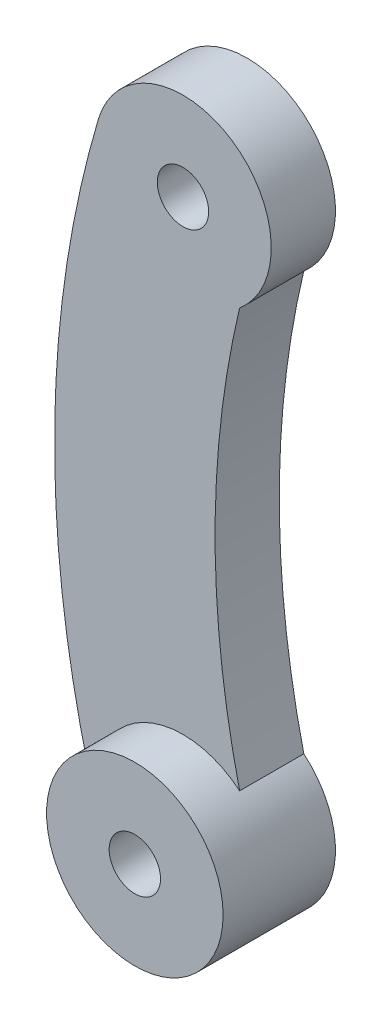
SolidWorks part; units mm, degrees
ref_plane "Ön Düzlem" through (0, 0, 0) normal (0, 0, 1) x (1, 0, 0)
ref_plane "Üst Düzlem" through (0, 0, 0) normal (0, 1, 0) x (1, 0, 0)
ref_plane "Sağ Düzlem" through (0, 0, 0) normal (1, 0, 0) x (0, 0, -1)
sketch "Çizim1" plane through (0, 0, 0) normal (0, 0, 1) x (1, 0, 0)
  line L0 (0, 34.5) -> (0, 0) construction
  line L1 (-8, 17.25) -> (34.0236, 17.25) construction
  arc A0 (-5.2737, -1.5614) -> (3.5302, 4.2175) centre (0, 0) ccw
  arc A1 (3.5302, 30.2825) -> (-5.2737, 36.0614) centre (0, 34.5) ccw
  arc A2 (-5.2737, 36.0614) -> (-5.2737, -1.5614) centre (58.2625, 17.25) ccw
  arc A3 (3.5302, 30.2825) -> (3.5302, 4.2175) centre (58.2625, 17.25) ccw
  circle A4 centre (0, 34.5) radius 1.6
  circle A5 centre (0, 0) radius 1.6
  dimension "D1" = 11
  dimension "D2" = 11
  dimension "D5" = 10
  dimension "D6" = 3.2
  dimension "D7" = 3.2
  dimension "D3" = 34.5
  dimension "D4" = 8
extrude "Yükseklik-Ekstrüzyon1" add sketch "Çizim1" along normal blind 4
sketch "Çizim2" plane through (0, 0, 4) normal (0, 0, 1) x (1, 0, 0)
  circle A0 centre (0, 0) radius 1.6
  circle A1 centre (0, 0) radius 5.5
  dimension "D1" = 3.2
  dimension "D2" = 11
extrude "Yükseklik-Ekstrüzyon2" add sketch "Çizim2" along normal blind 3
